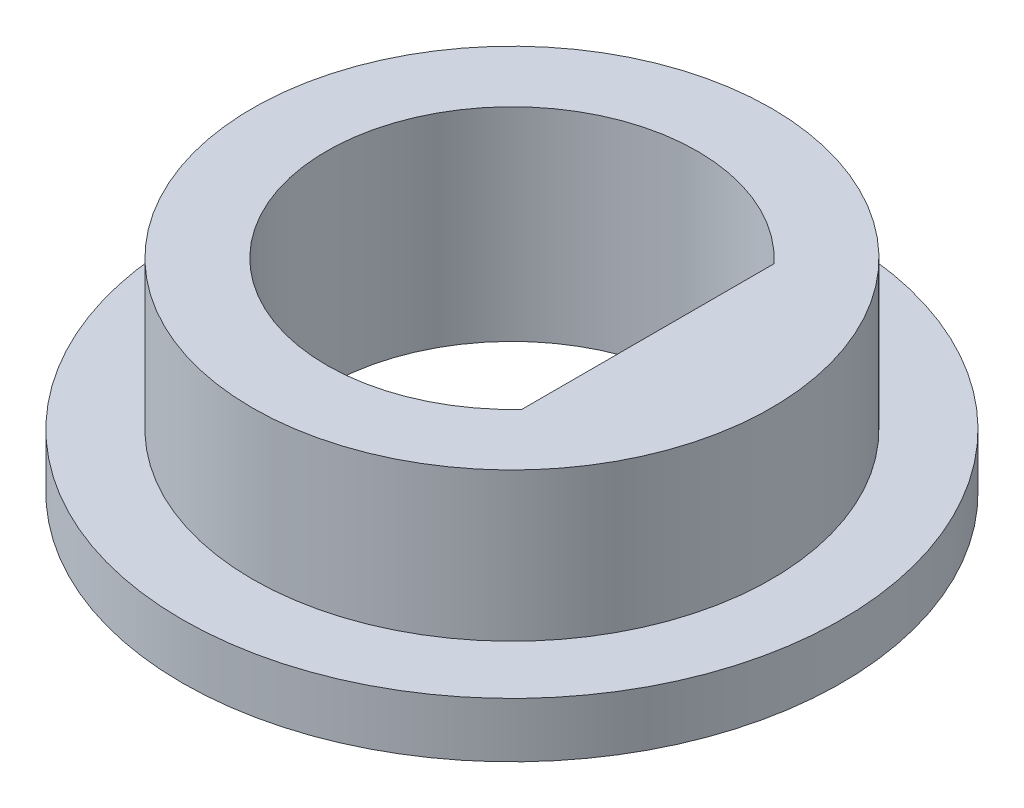
SolidWorks part; units mm, degrees
ref_plane "Front Plane" through (0, 0, 0) normal (0, 0, 1) x (1, 0, 0)
ref_plane "Top Plane" through (0, 0, 0) normal (0, 1, 0) x (1, 0, 0)
ref_plane "Right Plane" through (0, 0, 0) normal (1, 0, 0) x (0, 0, -1)
sketch "Sketch1" plane through (0, 0, 0) normal (0, 1, 0) x (1, 0, 0)
  circle A0 centre (0, 0) radius 6
  dimension "D1" = 12
extrude "Boss-Extrude1" add sketch "Sketch1" along normal blind 1
sketch "Sketch2" plane through (0, 1, 0) normal (0, 1, 0) x (1, 0, 0)
  circle A0 centre (0, 0) radius 4.725
  dimension "D1" = 9.45
extrude "Boss-Extrude2" add sketch "Sketch2" along normal blind 2.7
sketch "Sketch3" plane through (0, 3.7, 0) normal (0, 1, 0) x (1, 0, 0)
  line L1 (2.475, 2.2946) -> (2.475, -2.2946)
  arc A0 (2.475, 2.2946) -> (2.475, -2.2946) centre (0, 0) ccw
  point P7 (2.475, 0)
  dimension "D1" = 6.75
  dimension "D2" = 4.5891
extrude "Cut-Extrude1" cut sketch "Sketch3" against normal through all
